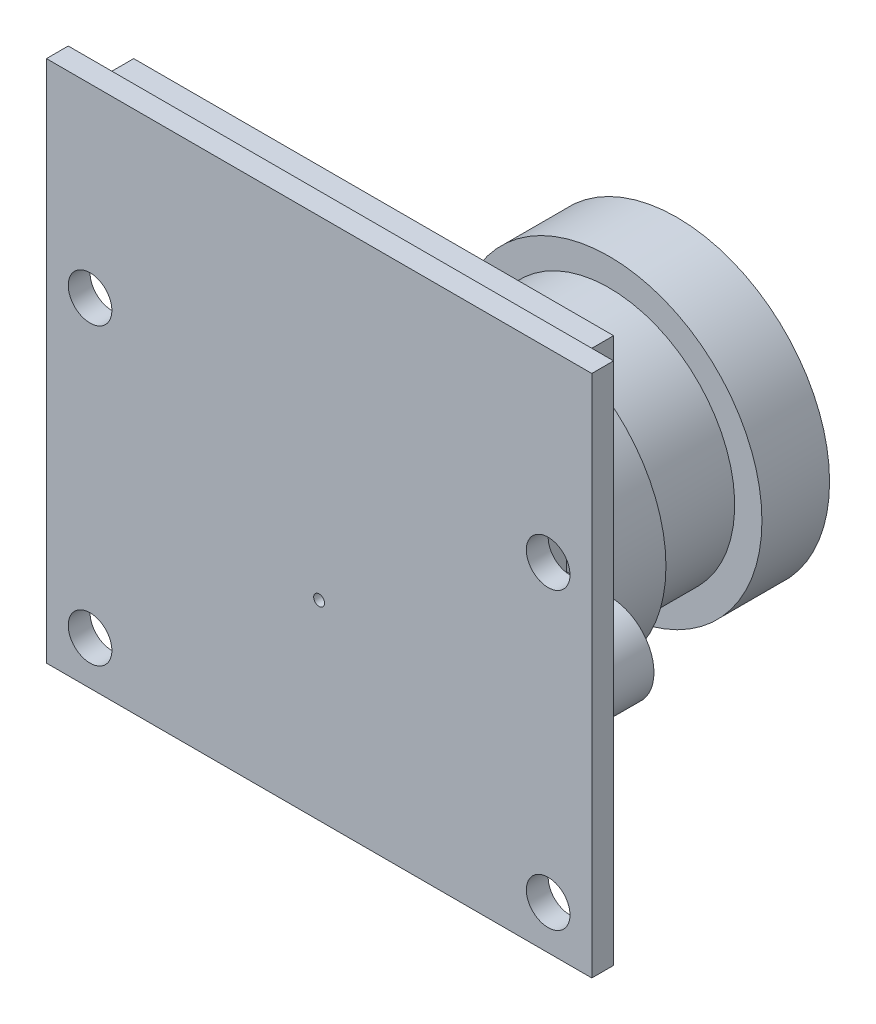
SolidWorks part; units mm, degrees
ref_plane "Спереди" through (0, 0, 0) normal (0, 0, 1) x (1, 0, 0)
ref_plane "Сверху" through (0, 0, 0) normal (0, 1, 0) x (1, 0, 0)
ref_plane "Справа" through (0, 0, 0) normal (1, 0, 0) x (0, 0, -1)
ref_plane "Плоскость4" through (0, 0, -1) normal (0, 0, -1) x (-1, 0, 0)
sketch "Эскиз1" plane through (0, 0, -1) normal (0, 0, -1) x (-1, 0, 0)
  line L0 (-25, 0) -> (0, 0)
  line L1 (0, 0) -> (0, 24)
  line L2 (0, 24) -> (-25, 24)
  line L3 (-25, 24) -> (-25, 0)
extrude "плата" add sketch "Эскиз1" against normal blind 1
sketch "Эскиз2" plane through (0, 0, -1) normal (0, 0, -1) x (-1, 0, 0)
  line L0 (-5.95, 10.75) -> (-3.95, 10.75)
  line L1 (-3.95, 6.75) -> (-5.95, 6.75)
  line L2 (-5.95, 6.75) -> (-5.95, 2.2)
  line L3 (-5.95, 2.2) -> (-19.05, 2.2)
  line L4 (-19.05, 2.2) -> (-19.05, 6.75)
  line L5 (-19.05, 6.75) -> (-21.05, 6.75)
  line L6 (-21.05, 10.75) -> (-19.05, 10.75)
  line L7 (-19.05, 10.75) -> (-19.05, 15.3)
  line L8 (-19.05, 15.3) -> (-5.95, 15.3)
  line L9 (-5.95, 15.3) -> (-5.95, 10.75)
  arc A0 (-3.95, 10.75) -> (-3.95, 6.75) centre (-3.95, 8.75) cw
  arc A1 (-21.05, 6.75) -> (-21.05, 10.75) centre (-21.05, 8.75) cw
extrude "выступ" add sketch "Эскиз2" along normal blind 3.8
sketch "Эскиз3" plane through (0, 0, -1) normal (0, 0, -1) x (-1, 0, 0)
  line L0 (-23.5, 18.6977) -> (-23.5, 23.5)
  line L1 (-23.5, 23.5) -> (-1.5, 23.5)
  line L2 (-1.5, 23.5) -> (-1.5, 18.6977)
  line L3 (-1.5, 18.6977) -> (-23.5, 18.6977)
extrude "разъем шлейфа" add sketch "Эскиз3" along normal blind 1.5
ref_plane "Плоскость5" through (0, 8.75, 0) normal (0, -1, 0) x (1, 0, 0)
sketch "Эскиз4" plane through (0, 8.75, 0) normal (0, -1, 0) x (1, 0, 0)
  line L0 (19.1, -4.8) -> (12.5, -4.8)
  line L1 (12.5, -4.8) -> (12.5, -16.4)
  line L2 (12.5, -16.4) -> (19.5, -16.4)
  line L3 (19.5, -16.4) -> (19.5, -13.3)
  line L4 (19.5, -13.3) -> (18.25, -13.3)
  line L5 (18.25, -13.3) -> (18.25, -9.3)
  line L6 (18.25, -9.3) -> (19.1, -9.3)
  line L7 (19.1, -9.3) -> (19.1, -4.8)
  line L8 (12.5, -4.8) -> (12.5, -16.4) construction
revolve "объектив" add sketch "Эскиз4" angle 360 about L8
hole_wizard "маленьекое отверстие" positions "Эскиз6" profile "Эскиз5" hole size "Ø0.5" standard "Ansi Metric"
sketch "Эскиз6" plane through (0, 0, 0) normal (0, 0, 1) x (1, 0, 0)
  point P0 (12.5, 8.75)
sketch "Эскиз5" plane through (12.5, 8.75, 0) normal (1, 0, 0) x (0, -1, 0)
  line L0 (0, 0) -> (0, 1)
  line L1 (0, 1) -> (0.25, 1)
  line L2 (0.25, 1) -> (0.25, 0)
  line L5 (0.25, 0) -> (0, 0)
  line L10 (0, 1) -> (-0.25, 1) construction
  line L11 (0, -6.35) -> (0, 107.95) construction
  dimension "Диаметр отверстия" = 0.5
  dimension "Глубина отверстия" = 1
  dimension "Угол заточки сверла" = 180
hole_wizard "крепежные отверстия" positions "Эскиз8" profile "Эскиз7" hole size "Ø2.0" standard "Ansi Metric"
sketch "Эскиз8" plane through (0, 0, 0) normal (0, 0, 1) x (1, 0, 0)
  point P0 (2, 2)
  point P1 (2, 15.5)
  point P2 (23, 15.5)
  point P3 (23, 2)
sketch "Эскиз7" plane through (2, 2, 0) normal (1, 0, 0) x (0, -1, 0)
  line L0 (0, 0) -> (0, 16.4)
  line L1 (0, 16.4) -> (1, 16.4)
  line L2 (1, 16.4) -> (1, 0)
  line L5 (1, 0) -> (0, 0)
  line L11 (0, -6.35) -> (0, 107.95) construction
  dimension "Диаметр сквозного отверстия" = 2
  dimension "Глубина сквозного отверстия" = 16.4
